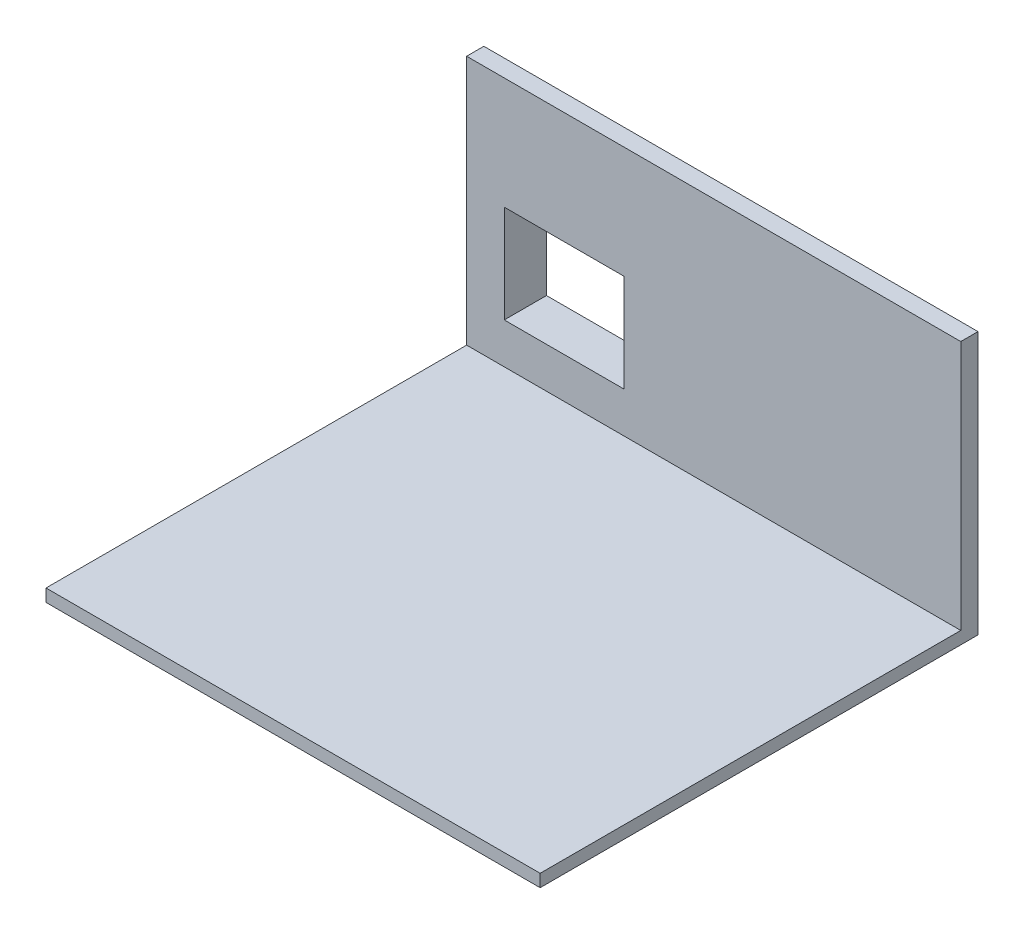
SolidWorks part; units mm, degrees
ref_plane "Front Plane" through (0, 0, 0) normal (0, 0, 1) x (1, 0, 0)
ref_plane "Top Plane" through (0, 0, 0) normal (0, 1, 0) x (1, 0, 0)
ref_plane "Right Plane" through (0, 0, 0) normal (1, 0, 0) x (0, 0, -1)
sketch "Sketch1" plane through (0, 0, 0) normal (0, 1, 0) x (1, 0, 0)
  line L1 (-6250, 1760.8696) -> (-3250, 1760.8696)
  line L2 (-6250, 1760.8696) -> (-6250, -1739.1304)
  line L3 (-6250, -1739.1304) -> (-3250, -1739.1304)
  line L4 (-3250, 1760.8696) -> (-3250, -1739.1304)
  dimension "D1" = 3500
  dimension "D2" = 3000
extrude "Boss-Extrude1" add sketch "Sketch1" along normal blind 100
sketch "Sketch2" plane through (0, 100, 0) normal (0, 1, 0) x (1, 0, 0)
  line L0 (-3250, -1739.1304) -> (-3250, 1760.8696) construction
  line L1 (-6250, 1760.8696) -> (-3250, 1760.8696)
  line L2 (-6250, 1760.8696) -> (-6250, 848.1787)
  line L3 (-6250, 848.1787) -> (-3250, 848.1787)
  line L4 (-3250, 1760.8696) -> (-3250, 848.1787)
extrude "Boss-Extrude2" add sketch "Sketch2" along normal blind 2000
sketch "Sketch3" plane through (0, 0, -1760.8696) normal (0, 0, -1) x (-1, 0, 0)
  line L1 (4902.7096, 1295.6958) -> (6039.2414, 1295.6958)
  line L2 (4902.7096, 1295.6958) -> (4902.7096, 334.8137)
  line L3 (4902.7096, 334.8137) -> (6039.2414, 334.8137)
  line L4 (6039.2414, 1295.6958) -> (6039.2414, 334.8137)
  line L5 (4992.7096, 1205.6958) -> (5949.2414, 1205.6958)
  line L6 (4992.7096, 1205.6958) -> (4992.7096, 424.8137)
  line L7 (4992.7096, 424.8137) -> (5949.2414, 424.8137)
  line L8 (5949.2414, 1205.6958) -> (5949.2414, 424.8137)
  dimension "D1" = 90
  dimension "D2" = 90
  dimension "D3" = 90
  dimension "D4" = 90
  dimension "D5" = 90
extrude "Boss-Extrude3" add sketch "Sketch3" along normal blind 200
sketch "Sketch4" plane through (0, 0, -848.1787) normal (0, 0, 1) x (1, 0, 0)
  line L1 (-6250, 2100) -> (-3250, 2100)
  line L2 (-6250, 2100) -> (-6250, 100)
  line L3 (-6250, 100) -> (-3250, 100)
  line L4 (-3250, 2100) -> (-3250, 100)
extrude "Cut-Extrude1" cut sketch "Sketch4" against normal blind 775
sketch "Sketch5" plane through (0, 0, -1760.8696) normal (0, 0, -1) x (-1, 0, 0)
  line L1 (4992.7096, 1205.6958) -> (5949.2414, 1205.6958)
  line L2 (4992.7096, 1205.6958) -> (4992.7096, 424.8137)
  line L3 (4992.7096, 424.8137) -> (5949.2414, 424.8137)
  line L4 (5949.2414, 1205.6958) -> (5949.2414, 424.8137)
extrude "Cut-Extrude2" cut sketch "Sketch5" against normal through all both and the other way through all
sketch "Sketch6" plane through (-3250, 0, 0) normal (1, 0, 0) x (0, 0, -1)
  line L0 (-1739.1304, 0) -> (1760.8696, 0) construction
  line L1 (1760.8696, 2100) -> (1623.1787, 2100)
  line L2 (1760.8696, 2100) -> (1760.8696, 0)
  line L3 (1760.8696, 0) -> (1620.9002, 0)
  line L5 (1623.1787, 100) -> (1623.1787, 2100)
  line L6 (-1739.1304, 0) -> (1623.1787, 0)
  line L7 (-1739.1304, 0) -> (-1739.1304, 100)
  line L8 (-1739.1304, 100) -> (1623.1787, 100)
  line M1 (1623.1787, 2100) -> (1623.1787, 100)
  line M2 (1623.1787, 100) -> (-1739.1304, 100)
  line M3 (-1739.1304, 100) -> (-1739.1304, 0)
  line M4 (-1739.1304, 0) -> (1760.8696, 0)
  line M5 (1760.8696, 0) -> (1760.8696, 2100)
  line M6 (1760.8696, 2100) -> (1623.1787, 2100)
extrude "Boss-Extrude4" add sketch "Sketch6" along normal blind 950 contours L3 M6 M1 M2 M3 M4 M5
